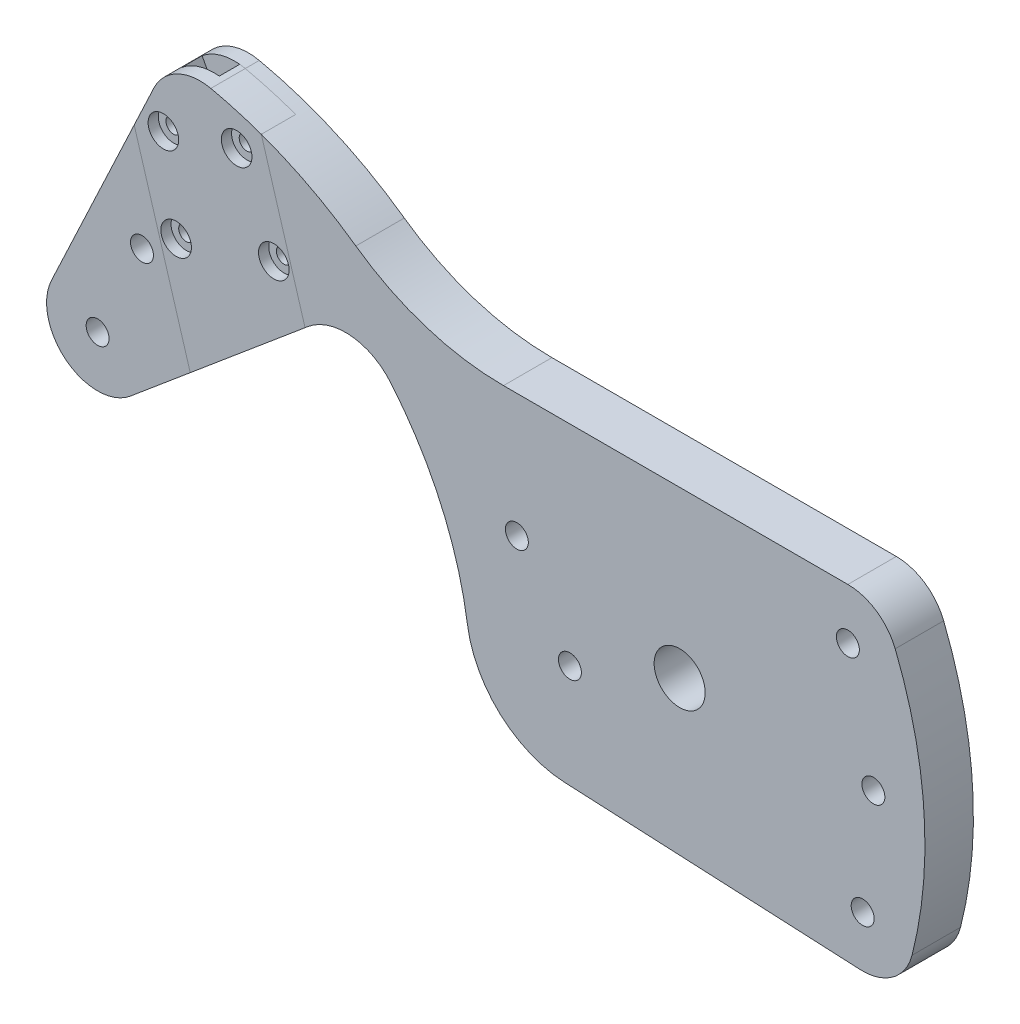
SolidWorks part; units mm, degrees
ref_plane "Front Plane" through (0, 0, 0) normal (0, 0, 1) x (1, 0, 0)
ref_plane "Top Plane" through (0, 0, 0) normal (0, 1, 0) x (1, 0, 0)
ref_plane "Right Plane" through (0, 0, 0) normal (1, 0, 0) x (0, 0, -1)
sketch "Sketch1" plane through (0, 0, 0) normal (0, 0, 1) x (1, 0, 0)
  line L1 (-5, -5) -> (5, -5) construction
  line L2 (-5, -5) -> (-5, 5) construction
  line L3 (-5, 5) -> (5, 5) construction
  line L4 (5, -5) -> (5, 5) construction
  line L5 (-5, -5) -> (5, 5) construction
  line L6 (-5, 5) -> (5, -5) construction
  line L7 (35.3984, -31.7883) -> (-22.5002, -28.984)
  line L9 (-114.4671, 24.4556) -> (-123.1671, 5.9556)
  line L10 (-107.6899, -5.9604) -> (-72.8648, 23.2613)
  line L11 (-114.4671, 24.4556) -> (-103.0859, 48.6569)
  line L16 (-65.4725, 14.4515) -> (-108.3178, -21.5) construction
  line L17 (50.9822, -33.5) -> (-177.2181, -33.5) construction
  line L20 (-34.5382, 32.4) -> (32.9822, 32.4)
  circle A0 centre (0, 0) radius 5
  circle A1 centre (-31.9178, 8.2) radius 2.25
  circle A2 centre (-21.5178, -8.7) radius 2.25
  circle A3 centre (32.9822, 22.4) radius 2.25
  circle A4 centre (37.9822, -0.1) radius 2.25
  circle A5 centre (35.8822, -21.8) radius 2.25
  circle A6 centre (35.8822, -21.8) radius 2.25 construction
  circle A7 centre (37.9822, -0.1) radius 2.25 construction
  circle A8 centre (32.9822, 22.4) radius 2.25 construction
  circle A9 centre (-31.9178, 8.2) radius 2.25 construction
  circle A10 centre (-21.5178, -8.7) radius 2.25 construction
  arc A12 (-41.6083, -11.6627) -> (-22.5002, -28.984) centre (-21.5178, -8.7) ccw
  arc A13 (32.5913, -31.6523) -> (28.0429, 32.4) centre (-33.3577, -4.1478) ccw construction
  arc A14 (45.5723, -24.2704) -> (42.2664, 26.1153) centre (-33.3577, -4.1478) ccw
  arc A15 (35.3984, -31.7883) -> (45.5723, -24.2704) centre (35.8822, -21.8) ccw
  arc A16 (42.2664, 26.1153) -> (32.9822, 32.4) centre (32.9822, 22.4) ccw
  circle A17 centre (-105.4178, 20.2) radius 2.25
  circle A18 centre (-33.3577, -4.1478) radius 81.4546 construction
  circle A19 centre (-114.1178, 1.7) radius 2.25
  circle A21 centre (-105.4178, 20.2) radius 2.25 construction
  circle A22 centre (-114.1178, 1.7) radius 2.25 construction
  circle A23 centre (-105.4178, 20.2) radius 10 construction
  arc A24 (-123.1671, 5.9556) -> (-107.6899, -5.9604) centre (-114.1178, 1.7) ccw
  arc A27 (-91.9187, 54.1744) -> (-103.0859, 48.6569) centre (-94.0366, 44.4013) ccw
  circle A31 centre (-33.3577, -4.1478) radius 71.4546 construction
  arc A32 (-41.6083, -11.6627) -> (-56.6627, 21.8438) centre (-108.3178, -21.5) ccw
  arc A33 (-31.0568, -26.628) -> (-91.9187, 54.1744) centre (-108.3178, -21.5) ccw
  arc A34 (-63.487, 41.6328) -> (-34.5382, 32.4) centre (-34.5382, 82.4) ccw
  arc A35 (-56.6627, 21.8438) -> (-72.8648, 23.2613) centre (-65.4725, 14.4515) ccw
  circle A36 centre (-65.4725, 14.4515) radius 10.5004 construction
  circle A37 centre (-108.3178, -21.5) radius 67.4309 construction
  circle A38 centre (-108.3178, -21.5) radius 77.4309 construction
  circle A39 centre (-108.3178, -21.5) radius 10.5004 construction
  circle A40 centre (-108.3178, -21.5) radius 11.5004 construction
  circle A41 centre (0, 0) radius 33 construction
  point P35 (50.3427, -4.5217)
  point P37 (37.1696, 16.7103)
  point P54 (-36.0565, -0.0269)
  point P75 (-40.8381, -1.4887)
  dimension "D1" = 10
  dimension "D3" = 10
  dimension "D5" = 50
  dimension "D7" = 40
  dimension "D4" = 10
  dimension "D2" = 10
  dimension "D8" = 1
extrude "Boss-Extrude1" add sketch "Sketch1" along normal mid plane 9.5 contours A0 L4 L3 | A0 L1 L4 | A0 L2 L1 | A0 L3 L2 | A35 A32 A12 A33 A27 L11 L9 A24 L10 A17 A19
sketch "Sketch2" plane through (0, 0, 0) normal (0, 0, 1) x (1, 0, 0)
  line L0 (-94.0366, 44.4013) -> (-96.9145, 53.9782) construction
  line L1 (-78.2271, 18.7618) -> (-72.8648, 23.2613)
  line L2 (-94.0366, 44.4013) -> (-84.6999, 13.3304) construction
  line L3 (-92.0846, 44.9879) -> (-78.2271, 18.7618)
  line L4 (-95.0124, 54.3536) -> (-94.0366, 44.4013) construction
  line L5 (-94.0366, 44.4013) -> (-90.5122, 8.4534) construction
  line L6 (-98.7084, 53.2429) -> (-94.0366, 44.4013) construction
  line L7 (-94.0366, 44.4013) -> (-79.7943, 17.4467) construction
  line L8 (-100.3823, 52.1299) -> (-95.9887, 43.8147)
  line L9 (-93.0022, 54.3476) -> (-92.0846, 44.9879)
  line L12 (-92.369, 6.8953) -> (-78.2271, 18.7618)
  line L13 (-107.6899, -5.9604) -> (-72.8648, 23.2613) construction
  line L14 (-101.3327, 53.9285) -> (-91.0539, 34.4751) construction
  line L15 (-93.2007, 56.3721) -> (-91.0539, 34.4751) construction
  line L16 (-95.9887, 43.8147) -> (-92.369, 6.8953)
  line L18 (-97.0194, 54.3274) -> (-78.2271, 18.7618) construction
  line L19 (-97.0194, 54.3274) -> (-92.369, 6.8953) construction
  line L20 (-92.369, 6.8953) -> (-107.6899, -5.9604)
  line L22 (-94.0366, 44.4013) -> (-90.3786, 7.0905) construction
  line L23 (-94.0366, 44.4013) -> (-79.9955, 17.8274) construction
  arc A0 (-93.0022, 54.3476) -> (-100.3823, 52.1299) centre (-94.0366, 44.4013) ccw
  arc A1 (-95.0124, 54.3536) -> (-98.7084, 53.2429) centre (-94.0366, 44.4013) ccw construction
  arc A2 (-93.2007, 56.3721) -> (-101.3327, 53.9285) centre (-94.0366, 44.4013) ccw construction
  arc A3 (-91.9187, 54.1744) -> (-103.0859, 48.6569) centre (-94.0366, 44.4013) ccw construction
  point P33 (-96.9145, 53.9782)
  dimension "D3" = 7
  dimension "D4" = 20
  dimension "D1" = 2
  dimension "D2" = 2
extrude "Cut-Extrude1" cut sketch "Sketch2" against normal mid plane 4
ref_plane "Plane1" through (-20.0256, 66.6414, 0) normal (-0.2878, 0.9577, 0) x (0.9577, 0.2878, 0)
sketch "Sketch4" plane through (0, 0, 4.75) normal (0, 0, 1) x (1, 0, 0)
  line L10 (-101.2193, 42.2429) -> (-86.8539, 46.5597) construction
  line L11 (-17.9186, 67.2745) -> (-22.1325, 66.0083) construction
  line L12 (-98.7212, 25.2426) -> (-79.5673, 30.9983) construction
  line L13 (-94.0366, 44.4013) -> (-89.1443, 28.1205) construction
  line L15 (-92.0846, 44.9879) -> (-93.0022, 54.3476)
  line L16 (-78.2271, 18.7618) -> (-92.0846, 44.9879)
  line L17 (-92.369, 6.8953) -> (-78.2271, 18.7618)
  line L18 (-95.9887, 43.8147) -> (-92.369, 6.8953)
  line L19 (-100.3823, 52.1299) -> (-95.9887, 43.8147)
  line L20 (-92.0846, 44.9879) -> (-93.0022, 54.3476) construction
  line L21 (-78.2271, 18.7618) -> (-92.0846, 44.9879) construction
  line L22 (-92.369, 6.8953) -> (-78.2271, 18.7618) construction
  line L23 (-95.9887, 43.8147) -> (-92.369, 6.8953) construction
  line L24 (-100.3823, 52.1299) -> (-95.9887, 43.8147) construction
  circle A0 centre (-98.7212, 25.2426) radius 1.5
  circle A1 centre (-101.2193, 42.2429) radius 1.5
  circle A2 centre (-86.8539, 46.5597) radius 1.5
  circle A3 centre (-79.5673, 30.9983) radius 1.5
  arc A7 (-93.0022, 54.3476) -> (-100.3823, 52.1299) centre (-94.0366, 44.4013) ccw
  arc A8 (-93.0022, 54.3476) -> (-100.3823, 52.1299) centre (-94.0366, 44.4013) ccw construction
  point P13 (-94.0366, 44.4013)
  dimension "D3" = 3
  dimension "D2" = 17
  dimension "D4" = 15
  dimension "D5" = 20
  dimension "D1" = 0
extrude "Cut-Extrude2" cut sketch "Sketch4" against normal through all
sketch "Sketch5" plane through (0, 0, 4.75) normal (0, 0, 1) x (1, 0, 0)
  circle A49 centre (-101.2193, 42.2429) radius 3
  circle A50 centre (-86.8539, 46.5597) radius 3
  circle A51 centre (-79.5673, 30.9983) radius 3
  circle A52 centre (-98.7212, 25.2426) radius 3
  dimension "D1" = 6
extrude "Cut-Extrude3" cut sketch "Sketch5" against normal blind 2
sketch "Sketch3" plane through (-20.0256, 66.6414, 0) normal (-0.2878, 0.9577, 0) x (0.9577, 0.2878, 0)
  line L0 (-90.7804, 2) -> (-63.7804, 2)
  line L1 (-63.7804, 2) -> (-63.7804, -4.75)
  line L2 (-72.4396, -4.75) -> (-48.8199, -4.75) construction
  line L3 (-90.7804, 2) -> (-90.7804, -4.75)
  line L4 (-116.2426, -4.75) -> (-84.7222, -4.75) construction
  line L11 (-79.3187, 2) -> (-75.2421, 2) construction
  point P3 (-77.2804, 2)
  point P11 (-77.2804, 2)
  dimension "D1" = 27
split "Split3" trim tools "Sketch3" bodies to split 111 resulting bodies 112 113
